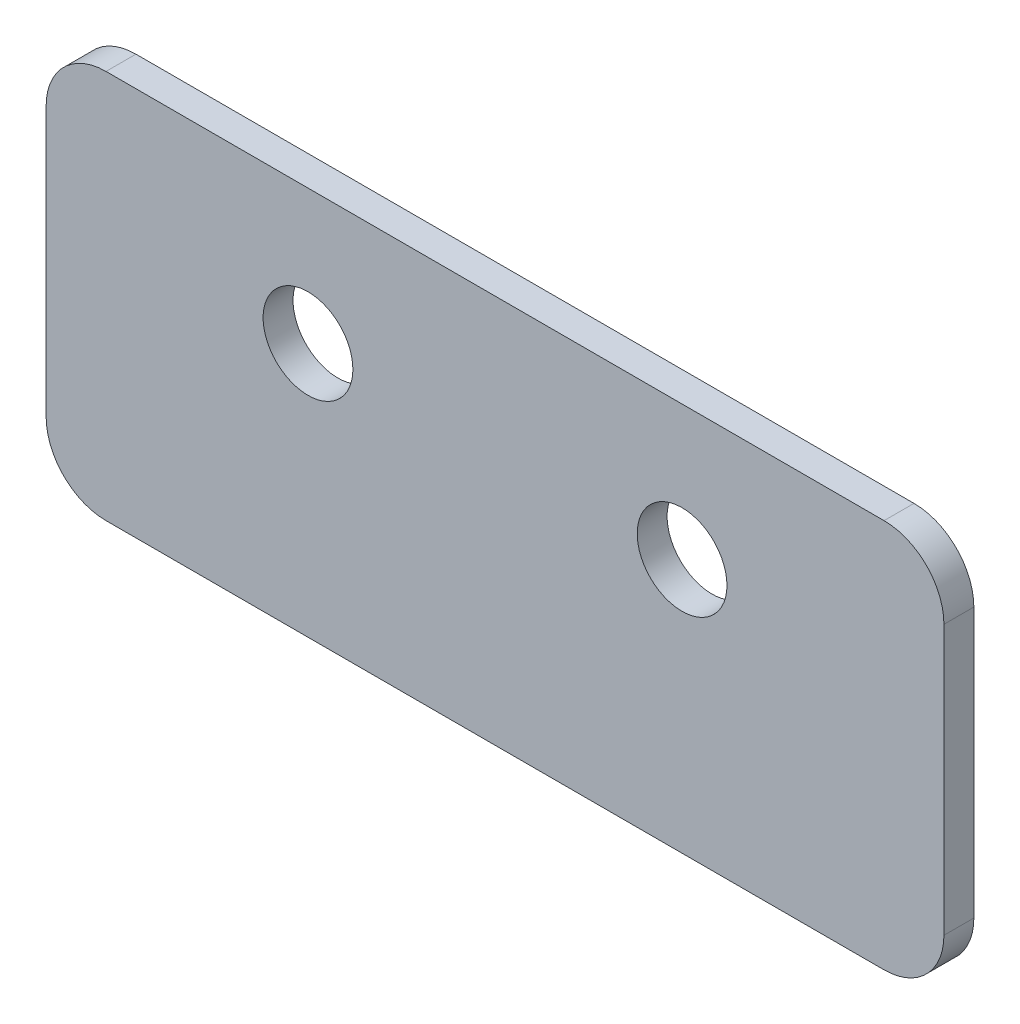
SolidWorks part; units mm, degrees
material "Circuit imprimé de calcul, simple"
ref_plane "Plan de face" through (0, 0, 0) normal (0, 0, 1) x (1, 0, 0)
ref_plane "Plan de dessus" through (0, 0, 0) normal (0, 1, 0) x (1, 0, 0)
ref_plane "Plan de droite" through (0, 0, 0) normal (1, 0, 0) x (0, 0, -1)
sketch "Esquisse1" plane through (0, 0, 0) normal (0, 0, 1) x (1, 0, 0)
  line L0 (0, 11.6953) -> (0, -11.1534) construction
  line L1 (-18.7028, 0) -> (18.4151, 0) construction
  line L2 (-6.25, 7.7182) -> (-6.25, -8.8833) construction
  line L3 (-13, 4.5) -> (13, 4.5)
  line L4 (-15, 2.5) -> (-15, -6.5)
  line L5 (-13, -8.5) -> (13, -8.5)
  line L6 (15, 2.5) -> (15, -6.5)
  line L7 (6.25, 7.7182) -> (6.25, -8.8833) construction
  circle A0 centre (-6.25, 0) radius 1.5
  circle A1 centre (6.25, 0) radius 1.5
  arc A2 (13, -8.5) -> (15, -6.5) centre (13, -6.5) ccw
  arc A3 (-15, -6.5) -> (-13, -8.5) centre (-13, -6.5) ccw
  arc A4 (13, 4.5) -> (15, 2.5) centre (13, 2.5) cw
  arc A5 (-13, 4.5) -> (-15, 2.5) centre (-13, 2.5) ccw
  dimension "D5" = 3
  dimension "D6" = 3
  dimension "D7" = 2
  dimension "D8" = 2
  dimension "D9" = 8.5
  dimension "D1" = 30
  dimension "D2" = 13
  dimension "D3" = 6.25
  dimension "D4" = 6.25
extrude "Boss.-Extru.1" add sketch "Esquisse1" along normal blind 1
